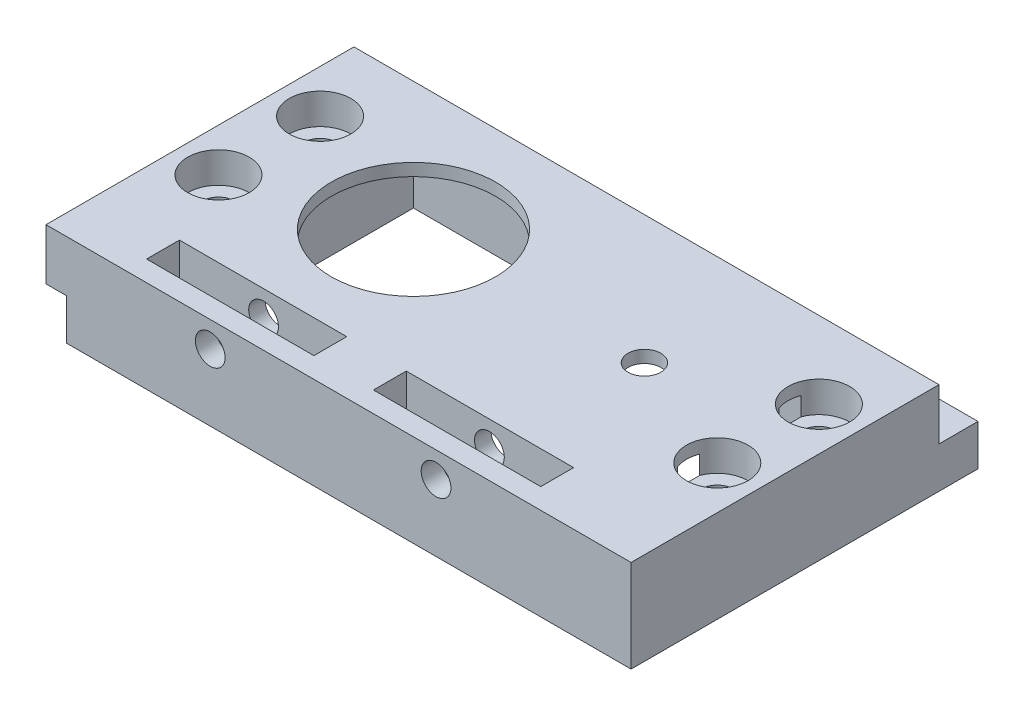
SolidWorks part; units mm, degrees
material "ABS"
ref_plane "Front Plane" through (0, 0, 0) normal (0, 0, 1) x (1, 0, 0)
ref_plane "Top Plane" through (0, 0, 0) normal (0, 1, 0) x (1, 0, 0)
ref_plane "Right Plane" through (0, 0, 0) normal (1, 0, 0) x (0, 0, -1)
sketch "Sketch1" plane through (0, 0, 0) normal (0, 1, 0) x (1, 0, 0)
  line L0 (-11.25, 0) -> (11.25, 0)
  line L1 (-25, -12.5) -> (25, -12.5)
  line L2 (-25, -12.5) -> (-25, 12.5)
  line L3 (-25, 12.5) -> (25, 12.5)
  line L4 (25, -12.5) -> (25, 12.5)
  line L5 (-25, -12.5) -> (25, 12.5) construction
  line L6 (-25, 12.5) -> (25, -12.5) construction
  circle A0 centre (-11.25, 0) radius 1.3
  circle A1 centre (11.25, 0) radius 4.5
  point P0 (0, 0)
  point P10 (0, 0)
  dimension "D3" = 2.6
  dimension "D4" = 9
  dimension "D1" = 25
  dimension "D2" = 50
  dimension "D5" = 22.5
extrude "Boss-Extrude1" add sketch "Sketch1" along normal mid plane 5
sketch "Sketch2" plane through (0, 0, 12.5) normal (0, 0, 1) x (1, 0, 0)
  line L0 (-25, 2.5) -> (-25, -2.5) construction
  line L1 (-25, -2.5) -> (25, -2.5)
  line L2 (-25, -2.5) -> (-25, 9.5)
  line L3 (-25, 9.5) -> (25, 9.5)
  line L4 (25, -2.5) -> (25, 9.5)
  line L5 (-25, -2.5) -> (25, -2.5) construction
  dimension "D1" = 50
  dimension "D2" = 12
extrude "Boss-Extrude2" add sketch "Sketch2" along normal blind 3
sketch "Sketch3" plane through (0, 9.5, 0) normal (0, 1, 0) x (1, 0, 0)
  line L0 (-25, -15.5) -> (-25, -12.5) construction
  line L1 (-25, -15.5) -> (25, -15.5)
  line L2 (-25, -15.5) -> (-25, 12.5)
  line L3 (-25, 12.5) -> (25, 12.5)
  line L4 (25, -15.5) -> (25, 12.5)
  line L5 (-25, 12.5) -> (25, 12.5) construction
extrude "Boss-Extrude3" add sketch "Sketch3" along normal blind 3
sketch "Sketch4" plane through (0, 12.5, 0) normal (0, 1, 0) x (1, 0, 0)
  line L0 (11.25, 0) -> (-11.25, 0)
  line L1 (-25, 12.5) -> (25, 12.5) construction
  line L2 (-25, -15.5) -> (-25, 12.5) construction
  circle A0 centre (11.25, 0) radius 1.3
  circle A1 centre (-11.25, 0) radius 1.3
  dimension "D1" = 2.6
  dimension "D2" = 2.6
  dimension "D3" = 11.25
  dimension "D4" = 12.5
  dimension "D5" = 13.75
extrude "Cut-Extrude1" cut sketch "Sketch4" against normal through all
sketch "Sketch5" plane through (0, -2.5, 0) normal (0, -1, 0) x (1, 0, 0)
  line L11 (21.45, -10.3) -> (21.45, 10.2) construction
  line L20 (0.95, 10.2) -> (41.95, 10.2) construction
  line L21 (0.95, 10.2) -> (0.95, -10.3) construction
  line L22 (0.95, -10.3) -> (41.95, -10.3) construction
  line L23 (41.95, 10.2) -> (41.95, -10.3) construction
  line L24 (-5.05, 16.2) -> (47.95, 16.2)
  line L25 (47.95, 16.2) -> (47.95, -16.3)
  line L26 (-5.05, -16.3) -> (47.95, -16.3)
  line L27 (-5.05, 16.2) -> (-5.05, -16.3)
  line L28 (0.45, 10.7) -> (42.45, 10.7)
  line L29 (42.45, 10.7) -> (42.45, -10.8)
  line L30 (0.45, -10.8) -> (42.45, -10.8)
  line L31 (0.45, 10.7) -> (0.45, -10.8)
  circle A5 centre (11.25, 0) radius 7.5 construction
  circle A6 centre (45.75, -5) radius 1.6
  circle A7 centre (45.75, 4.9) radius 1.6
  circle A8 centre (-2.85, 4.9) radius 1.6
  circle A9 centre (-2.85, -5) radius 1.6
  dimension "D4" = 10.3
  dimension "D5" = 10.3
  dimension "D8" = 3.8
  dimension "D9" = 5.3
  dimension "D1" = 15
  dimension "D6" = 3.2
  dimension "D7" = 3.2
  dimension "D2" = 41
  dimension "D3" = 20.5
  dimension "D10" = 5.3
  dimension "D11" = 6
  dimension "D12" = 0.5
extrude "Boss-Extrude4" add sketch "Sketch5" along normal blind 4
sketch "Sketch7" plane through (0, -2.5, 0) normal (0, -1, 0) x (1, 0, 0)
  circle A0 centre (11.25, 0) radius 8
  dimension "D1" = 16
extrude "Cut-Extrude2" cut sketch "Sketch7" against normal up to surface (5 mm away) up to face at (11.25, 2.5, 4.5)
sketch "Sketch8" plane through (0, -2.5, 0) normal (0, -1, 0) x (1, 0, 0)
  line L4 (0.45, 10.7) -> (0.45, -10.8)
  line L5 (0.45, 10.7) -> (0.45, -10.8)
  line L6 (0.45, -10.8) -> (25, -10.8)
  line L7 (25, -10.8) -> (25, 10.7)
  line L11 (25, -10.8) -> (25, 10.7)
  line L12 (0.45, -10.8) -> (25, -10.8)
  line L13 (25, 10.7) -> (0.45, 10.7)
  line L14 (25, 10.7) -> (0.45, 10.7)
  dimension "D1" = 0
extrude "Cut-Extrude3" cut sketch "Sketch8" against normal blind 3.8
sketch "Sketch9" plane through (25, 0, 0) normal (1, 0, 0) x (0, 0, -1)
  line L0 (-12.5, 2.5) -> (-15.5, 2.5)
  line L1 (-15.5, 2.5) -> (-16.2, 2.5)
  line L2 (-16.2, 2.5) -> (-16.2, -2.5)
  line L3 (-16.2, -2.5) -> (-15.5, -2.5)
  line L12 (-10.7, 1.3) -> (10.8, 1.3)
  line L13 (-10.7, -2.5) -> (-10.7, 1.3)
  line L14 (10.8, -2.5) -> (12.5, -2.5)
  line L15 (12.5, -2.5) -> (12.5, 2.5)
  line L16 (12.5, 2.5) -> (-12.5, 2.5)
  line L17 (-12.5, 2.5) -> (-12.5, 9.5)
  line L18 (-12.5, 9.5) -> (12.5, 9.5)
  line L19 (12.5, 9.5) -> (12.5, 12.5)
  line L20 (12.5, 12.5) -> (-15.5, 12.5)
  line L21 (-15.5, 12.5) -> (-15.5, -2.5)
  line L22 (-15.5, -2.5) -> (-10.7, -2.5)
  line L23 (-10.7, -2.5) -> (-10.7, 1.3)
  line L24 (-10.7, 1.3) -> (10.8, 1.3)
  line L26 (10.8, -2.5) -> (12.5, -2.5)
  line L27 (12.5, -2.5) -> (12.5, 2.5)
  line L28 (12.5, 2.5) -> (-12.5, 2.5)
  line L29 (-12.5, 2.5) -> (-12.5, 9.5)
  line L30 (-12.5, 9.5) -> (12.5, 9.5)
  line L31 (12.5, 9.5) -> (12.5, 12.5)
  line L32 (12.5, 12.5) -> (-15.5, 12.5)
  line L33 (-15.5, 12.5) -> (-15.5, -2.5)
  line L34 (-15.5, -2.5) -> (-10.7, -2.5)
  line L40 (10.8, 1.3) -> (10.8, -2.5)
  line L41 (10.8, 1.3) -> (10.8, -2.5)
  dimension "D1" = 0
extrude "Boss-Extrude6" add sketch "Sketch9" along normal up to surface (22.95 mm away) up to face at (47.95, -4.5, -0.05)
sketch "Sketch10" plane through (47.95, 0, 0) normal (1, 0, 0) x (0, 0, -1)
  line L6 (16.3, -2.5) -> (12.5, -2.5)
  line L7 (12.5, -2.5) -> (12.5, 2.5)
  line L8 (12.5, 2.5) -> (-16.2, 2.5)
  line L9 (-16.2, 2.5) -> (-16.2, -6.5)
  line L10 (-16.2, -6.5) -> (16.3, -6.5)
  line L11 (16.3, -6.5) -> (16.3, -2.5)
  line L12 (16.3, -2.5) -> (12.5, -2.5)
  line L13 (12.5, -2.5) -> (12.5, 2.5)
  line L14 (12.5, 2.5) -> (-16.2, 2.5)
  line L15 (-16.2, 2.5) -> (-16.2, -6.5)
  line L16 (-16.2, -6.5) -> (16.3, -6.5)
  line L17 (16.3, -6.5) -> (16.3, -2.5)
  dimension "D1" = 0
extrude "Boss-Extrude7" add sketch "Sketch10" along normal blind 2
sketch "Sketch11" plane through (0, 1.3, 0) normal (0, -1, 0) x (1, 0, 0)
  circle A0 centre (-2.85, 4.9) radius 1.6 construction
  circle A1 centre (-2.85, -5) radius 1.6 construction
  circle A2 centre (45.75, 4.9) radius 1.6 construction
  circle A3 centre (45.75, -5) radius 1.6 construction
  circle A4 centre (-2.85, 4.9) radius 1.6
  circle A5 centre (-2.85, -5) radius 1.6
  circle A6 centre (45.75, 4.9) radius 1.6
  circle A7 centre (45.75, -5) radius 1.6
extrude "Cut-Extrude4" cut sketch "Sketch11" against normal up to surface (1.2 mm away) up to face at (11.25, 2.5, 8)
sketch "Sketch12" plane through (0, 1.3, 0) normal (0, -1, 0) x (1, 0, 0)
  line L0 (49.95, 16.2) -> (49.95, -16.3) construction
  line L1 (42.95, 10.7) -> (49.95, 10.7)
  line L2 (42.95, 10.7) -> (42.95, -10.3)
  line L3 (42.95, -10.3) -> (49.95, -10.3)
  line L4 (49.95, 10.7) -> (49.95, -10.3)
  line L6 (0.45, 10.7) -> (0.45, -10.8) construction
  line L7 (47.95, 10.7) -> (0.45, 10.7) construction
  line L8 (0.45, 10.7) -> (42.45, 10.7) construction
  circle A0 centre (45.75, 4.9) radius 1.6 construction
  circle A1 centre (45.75, -5) radius 1.6 construction
  circle A2 centre (45.75, 4.9) radius 1.6
  circle A3 centre (45.75, -5) radius 1.6
  dimension "D1" = 42.5
  dimension "D2" = 21
extrude "Boss-Extrude8" add sketch "Sketch12" along normal up to surface (7.8 mm away) up to face at (22.45, -6.5, -0.05)
sketch "Sketch13" plane through (25, 0, 0) normal (-1, 0, 0) x (0, 0, 1)
  line L1 (15.5, 2.5) -> (16.2, 2.5)
  line L2 (15.5, 2.5) -> (15.5, -6.5)
  line L3 (15.5, -6.5) -> (16.2, -6.5)
  line L4 (16.2, 2.5) -> (15.5, 2.5)
  line L5 (15.5, 2.5) -> (15.5, -2.5)
  line L6 (15.5, -2.5) -> (16.2, -2.5)
  line L7 (16.2, -2.5) -> (16.2, 2.5)
  line L8 (16.2, 2.5) -> (15.5, 2.5)
  line L9 (15.5, 2.5) -> (15.5, -2.5)
  line L11 (16.2, -2.5) -> (16.2, 2.5)
  line L12 (16.2, 2.5) -> (16.2, -6.5)
  line M5 (16.2, 2.5) -> (15.5, 2.5)
  line M6 (15.5, 2.5) -> (15.5, -2.5)
  line M7 (15.5, -2.5) -> (16.2, -2.5)
  line M8 (16.2, -2.5) -> (16.2, 2.5)
  dimension "D1" = 0
extrude "Cut-Extrude5" cut sketch "Sketch13" against normal through all both and the other way through all contours M8 M5 M6 M7 | L12 L2 L3 M7
sketch "Sketch14" plane through (-25, 0, 0) normal (-1, 0, 0) x (0, 0, 1)
  line L0 (15.5, 12.5) -> (15.5, -2.5) construction
  line L1 (-12.5, 12.5) -> (15.5, 12.5)
  line L2 (-12.5, 12.5) -> (-12.5, 2.5)
  line L3 (-12.5, 2.5) -> (15.5, 2.5)
  line L4 (15.5, 12.5) -> (15.5, 2.5)
  line L5 (12.5, 2.5) -> (-12.5, 2.5) construction
extrude "Cut-Extrude6" cut sketch "Sketch14" against normal through all both and the other way through all
sketch "Sketch15" plane through (0, 2.5, 0) normal (0, 1, 0) x (1, 0, 0)
  circle A0 centre (-2.85, 5) radius 1.6
  circle A1 centre (-2.85, -4.9) radius 1.6
  dimension "D1" = 3.2
  dimension "D2" = 3.2
sketch "Sketch16" plane through (0, 2.5, 0) normal (0, 1, 0) x (1, 0, 0)
  circle A0 centre (-2.85, 5) radius 3
  circle A1 centre (-2.85, -4.9) radius 3
  circle A2 centre (45.75, 5) radius 3
  circle A3 centre (45.75, -4.9) radius 3
  dimension "D1" = 6
  dimension "D2" = 6
  dimension "D3" = 6
  dimension "D4" = 6
extrude "Cut-Extrude8" cut sketch "Sketch16" against normal blind 3
extrude "Cut-Extrude9" cut sketch "Sketch15" against normal up to surface (5 mm away) up to face at (44.45, -2.5, -3.4667)
sketch "Sketch17" plane through (0, 0, 15.5) normal (0, 0, 1) x (1, 0, 0)
  line L1 (49.95, 2.5) -> (-25, 2.5) construction
  line L2 (-5.05, 2.5) -> (0.75, 2.5)
  line L3 (-5.05, 2.5) -> (-5.05, -2.5)
  line L4 (-5.05, -2.5) -> (0.75, -2.5)
  line L5 (0.75, 2.5) -> (0.75, -2.5)
  line L7 (-5.05, 2.5) -> (44.95, 2.5)
  line L8 (22.85, 2.5) -> (17.05, 2.5)
  line L9 (22.85, 2.5) -> (22.85, -2.5)
  line L10 (22.85, -2.5) -> (17.05, -2.5)
  line L11 (17.05, 2.5) -> (17.05, -2.5)
  line L12 (44.95, 2.5) -> (39.15, 2.5)
  line L13 (44.95, 2.5) -> (44.95, -2.5)
  line L14 (44.95, -2.5) -> (39.15, -2.5)
  line L15 (39.15, 2.5) -> (39.15, -2.5)
  line L16 (44.95, -2.5) -> (-5.05, -2.5)
  line L17 (-5.05, -6.5) -> (-5.05, -2.5) construction
  point P17 (19.95, -2.5)
  point P18 (19.95, -2.5)
  line M14 (49.95, 2.5) -> (-25, 2.5)
  dimension "D1" = 5
  dimension "D2" = 5.8
  dimension "D3" = 5.8
  dimension "D4" = 5.8
  dimension "D5" = 50
extrude "Cut-Extrude10" cut sketch "Sketch17" against normal blind 3.2 contours L16 L11 L5 M14 | L16 L15 L7 L9
sketch "Sketch18" plane through (0, 0, 12.3) normal (0, 0, 1) x (1, 0, 0)
  line L3 (39.15, 2.5) -> (22.85, 2.5) construction
  line L4 (17.05, 2.5) -> (0.75, 2.5) construction
  circle A0 centre (8.95, 0) radius 1.45
  circle A1 centre (30.95, 0) radius 1.45
  dimension "D1" = 2.9
  dimension "D2" = 2.9
  dimension "D3" = 22
  dimension "D4" = 14
  dimension "D5" = 2.5
  dimension "D6" = 2.5
  dimension "D7" = 14
extrude "Cut-Extrude11" cut sketch "Sketch18" against normal blind 5
sketch "Sketch19" plane through (0, 2.5, 0) normal (0, 1, 0) x (1, 0, 0)
  line L0 (0.75, -12.3) -> (0.75, -15.5) construction
  line L1 (17.05, -12.3) -> (0.75, -12.3) construction
  circle A0 centre (33.75, 0) radius 1.6
  dimension "D1" = 3.2
  dimension "D2" = 33
  dimension "D3" = 12.3
extrude "Cut-Extrude12" cut sketch "Sketch19" against normal through all both and the other way through all
sketch "Sketch20" plane through (0, 0, 15.5) normal (0, 0, 1) x (1, 0, 0)
  line L0 (0.75, 2.5) -> (-25, 2.5) construction
  line L1 (-25, -2.5) -> (-7.05, -2.5)
  line L2 (-25, -2.5) -> (-25, 2.5)
  line L3 (-25, 2.5) -> (-7.05, 2.5)
  line L4 (-7.05, -2.5) -> (-7.05, 2.5)
  line L6 (-5.05, -6.5) -> (-5.05, -2.5) construction
  dimension "D1" = 2
extrude "Cut-Extrude14" cut sketch "Sketch20" against normal through all both and the other way through all
sketch "Sketch21" plane through (0, 0, 15.5) normal (0, 0, 1) x (1, 0, 0)
  line L0 (0.75, 2.5) -> (39.15, 2.5)
  line L14 (0.75, 2.5) -> (-7.05, 2.5)
  line L15 (-7.05, 2.5) -> (-7.05, -2.5)
  line L16 (-7.05, -2.5) -> (-5.05, -2.5)
  line L17 (-5.05, -2.5) -> (-5.05, -6.5)
  line L18 (-5.05, -6.5) -> (49.95, -6.5)
  line L19 (49.95, -6.5) -> (49.95, 2.5)
  line L20 (49.95, 2.5) -> (39.15, 2.5)
  line L21 (39.15, 2.5) -> (39.15, -2.5)
  line L22 (39.15, -2.5) -> (22.85, -2.5)
  line L23 (22.85, -2.5) -> (22.85, 2.5)
  line L24 (22.85, 2.5) -> (17.05, 2.5)
  line L25 (17.05, 2.5) -> (17.05, -2.5)
  line L26 (17.05, -2.5) -> (0.75, -2.5)
  line L27 (0.75, -2.5) -> (0.75, 2.5)
  line L28 (0.75, 2.5) -> (-7.05, 2.5)
  line L29 (-7.05, 2.5) -> (-7.05, -2.5)
  line L30 (-7.05, -2.5) -> (-5.05, -2.5)
  line L31 (-5.05, -2.5) -> (-5.05, -6.5)
  line L32 (-5.05, -6.5) -> (49.95, -6.5)
  line L33 (49.95, -6.5) -> (49.95, 2.5)
  line L34 (49.95, 2.5) -> (39.15, 2.5)
  line L35 (39.15, 2.5) -> (39.15, -2.5) construction
  line L36 (39.15, -2.5) -> (22.85, -2.5) construction
  line L37 (22.85, -2.5) -> (22.85, 2.5) construction
  line L38 (22.85, 2.5) -> (17.05, 2.5)
  line L39 (17.05, 2.5) -> (17.05, -2.5) construction
  line L40 (17.05, -2.5) -> (0.75, -2.5) construction
  line L41 (0.75, -2.5) -> (0.75, 2.5) construction
  circle A0 centre (8.95, 0) radius 1.45 construction
  circle A1 centre (8.95, 0) radius 1.45
  circle A2 centre (30.95, 0) radius 1.45 construction
  circle A3 centre (30.95, 0) radius 1.45
  line M15 (0.75, 2.5) -> (-7.05, 2.5)
  line M16 (-7.05, 2.5) -> (-7.05, -2.5)
  line M17 (-7.05, -2.5) -> (-5.05, -2.5)
  line M18 (-5.05, -2.5) -> (-5.05, -6.5)
  line M19 (-5.05, -6.5) -> (49.95, -6.5)
  line M20 (49.95, -6.5) -> (49.95, 2.5)
  line M21 (49.95, 2.5) -> (39.15, 2.5)
  line M22 (39.15, 2.5) -> (39.15, -2.5)
  line M23 (39.15, -2.5) -> (22.85, -2.5)
  line M24 (22.85, -2.5) -> (22.85, 2.5)
  line M25 (22.85, 2.5) -> (17.05, 2.5)
  line M26 (17.05, 2.5) -> (17.05, -2.5)
  line M27 (17.05, -2.5) -> (0.75, -2.5)
  line M28 (0.75, -2.5) -> (0.75, 2.5)
  dimension "D1" = 0
extrude "Boss-Extrude11" add sketch "Sketch21" along normal blind 2 contours L0 A1 M28 M27 M26 | M28 M15 M16 M17 M18 M19 M20 M21 M22 M23 M24 M25 M26 M27 | L0 A3 M24 M23 M22
